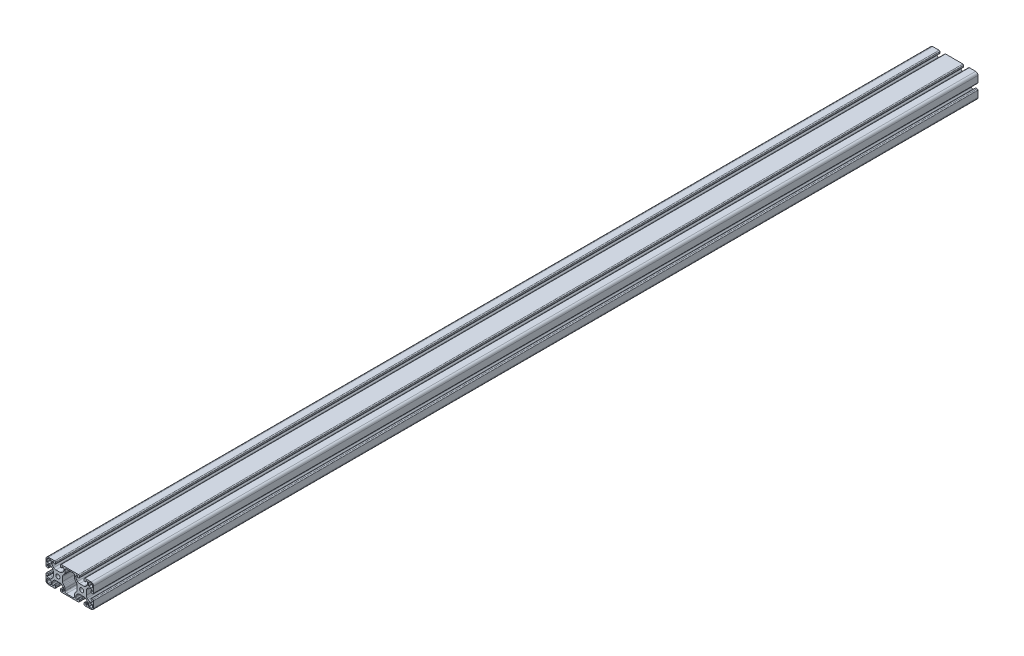
SolidWorks part; units mm, degrees
ref_plane "Plan de face" through (0, 0, 0) normal (0, 0, 1) x (1, 0, 0)
ref_plane "Plan de dessus" through (0, 0, 0) normal (0, 1, 0) x (1, 0, 0)
ref_plane "Plan de droite" through (0, 0, 0) normal (1, 0, 0) x (0, 0, -1)
ref_plane "Plan1" through (0, 0, 20) normal (0, 0, 1) x (1, 0, 0)
sketch "Esquisse1" plane through (0, 0, 20) normal (0, 0, 1) x (1, 0, 0)
  line L0 (66.5, 4.5) -> (65, 4.5)
  line L1 (64, 3.5) -> (64, 1.5)
  line L2 (65.5, 0) -> (76, 0)
  line L3 (80, 4) -> (80, 14.5)
  line L4 (78.5, 16) -> (76.5, 16)
  line L5 (75.5, 15) -> (75.5, 13.5)
  line L6 (76, 13) -> (77.5, 13)
  line L7 (75.5, 10) -> (74.1924, 10)
  line L8 (70.6569, 11.4645) -> (69.2145, 12.9069)
  line L9 (67.75, 16.4424) -> (67.75, 23.5576)
  line L10 (69.2145, 27.0931) -> (70.6569, 28.5355)
  line L11 (74.1924, 30) -> (75.5, 30)
  line L12 (77.5, 27) -> (76, 27)
  line L13 (75.5, 26.5) -> (75.5, 25)
  line L14 (76.5, 24) -> (78.5, 24)
  line L15 (80, 25.5) -> (80, 36)
  line L16 (76, 40) -> (65.5, 40)
  line L17 (64, 38.5) -> (64, 36.5)
  line L18 (65, 35.5) -> (66.5, 35.5)
  line L19 (67, 36) -> (67, 37.5)
  line L20 (70, 35.5) -> (70, 34.1924)
  line L21 (68.5355, 30.6569) -> (67.0931, 29.2145)
  line L22 (63.5576, 27.75) -> (56.4424, 27.75)
  line L23 (52.9069, 29.2145) -> (51.4645, 30.6569)
  line L24 (50, 34.1924) -> (50, 35.5)
  line L25 (53, 37.5) -> (53, 36)
  line L26 (53.5, 35.5) -> (55, 35.5)
  line L27 (56, 36.5) -> (56, 38.5)
  line L28 (54.5, 40) -> (25.5, 40)
  line L29 (24, 38.5) -> (24, 36.5)
  line L30 (25, 35.5) -> (26.5, 35.5)
  line L31 (27, 36) -> (27, 37.5)
  line L32 (30, 35.5) -> (30, 34.1924)
  line L33 (28.5355, 30.6569) -> (27.0931, 29.2145)
  line L34 (23.5576, 27.75) -> (16.4424, 27.75)
  line L35 (12.9069, 29.2145) -> (11.4645, 30.6569)
  line L36 (10, 34.1924) -> (10, 35.5)
  line L37 (13, 37.5) -> (13, 36)
  line L38 (13.5, 35.5) -> (15, 35.5)
  line L39 (16, 36.5) -> (16, 38.5)
  line L40 (14.5, 40) -> (4, 40)
  line L41 (0, 36) -> (0, 25.5)
  line L42 (1.5, 24) -> (3.5, 24)
  line L43 (4.5, 25) -> (4.5, 26.5)
  line L44 (4, 27) -> (2.5, 27)
  line L45 (4.5, 30) -> (5.8076, 30)
  line L46 (9.3431, 28.5355) -> (10.7855, 27.0931)
  line L47 (12.25, 23.5576) -> (12.25, 16.4424)
  line L48 (10.7855, 12.9069) -> (9.3431, 11.4645)
  line L49 (5.8076, 10) -> (4.5, 10)
  line L50 (2.5, 13) -> (4, 13)
  line L51 (4.5, 13.5) -> (4.5, 15)
  line L52 (3.5, 16) -> (1.5, 16)
  line L53 (0, 14.5) -> (0, 4)
  line L54 (4, 0) -> (14.5, 0)
  line L55 (16, 1.5) -> (16, 3.5)
  line L56 (15, 4.5) -> (13.5, 4.5)
  line L57 (13, 4) -> (13, 2.5)
  line L58 (10, 4.5) -> (10, 5.8076)
  line L59 (11.4645, 9.3431) -> (12.9069, 10.7855)
  line L60 (16.4424, 12.25) -> (23.5576, 12.25)
  line L61 (27.0931, 10.7855) -> (28.5355, 9.3431)
  line L62 (30, 5.8076) -> (30, 4.5)
  line L63 (27, 2.5) -> (27, 4)
  line L64 (26.5, 4.5) -> (25, 4.5)
  line L65 (24, 3.5) -> (24, 1.5)
  line L66 (25.5, 0) -> (54.5, 0)
  line L67 (56, 1.5) -> (56, 3.5)
  line L68 (55, 4.5) -> (53.5, 4.5)
  line L69 (53, 4) -> (53, 2.5)
  line L70 (50, 4.5) -> (50, 5.8076)
  line L71 (51.4645, 9.3431) -> (52.9069, 10.7855)
  line L72 (56.4424, 12.25) -> (63.5576, 12.25)
  line L73 (67.0931, 10.7855) -> (68.5355, 9.3431)
  line L74 (70, 5.8076) -> (70, 4.5)
  line L75 (67, 2.5) -> (67, 4)
  line L76 (31.8, 4.5) -> (31.8, 8.2503)
  line L77 (30.3355, 11.7858) -> (29.2145, 12.9069)
  line L78 (27.75, 16.4424) -> (27.75, 23.5576)
  line L79 (29.2145, 27.0931) -> (30.3355, 28.2142)
  line L80 (31.8, 31.7497) -> (31.8, 35.5)
  line L81 (34.3, 38) -> (45.7, 38)
  line L82 (48.2, 35.5) -> (48.2, 31.7497)
  line L83 (49.6645, 28.2142) -> (50.7855, 27.0931)
  line L84 (52.25, 23.5576) -> (52.25, 16.4424)
  line L85 (50.7855, 12.9069) -> (49.6645, 11.7858)
  line L86 (48.2, 8.2503) -> (48.2, 4.5)
  line L87 (45.7, 2) -> (34.3, 2)
  line L88 (7.7, 1.8) -> (4, 1.8)
  line L89 (1.8, 4) -> (1.8, 7.7)
  line L90 (2.3, 8.2) -> (7.7, 8.2)
  line L91 (8.2, 7.7) -> (8.2, 2.3)
  line L92 (72.3, 38.2) -> (76, 38.2)
  line L93 (78.2, 36) -> (78.2, 32.3)
  line L94 (77.7, 31.8) -> (72.3, 31.8)
  line L95 (71.8, 32.3) -> (71.8, 37.7)
  line L96 (78.2, 7.7) -> (78.2, 4)
  line L97 (76, 1.8) -> (72.3, 1.8)
  line L98 (71.8, 2.3) -> (71.8, 7.7)
  line L99 (72.3, 8.2) -> (77.7, 8.2)
  line L100 (1.8, 32.3) -> (1.8, 36)
  line L101 (4, 38.2) -> (7.7, 38.2)
  line L102 (8.2, 37.7) -> (8.2, 32.3)
  line L103 (7.7, 31.8) -> (2.3, 31.8)
  arc A0 (67, 4) -> (66.5, 4.5) centre (66.5, 4) ccw
  arc A1 (65, 4.5) -> (64, 3.5) centre (65, 3.5) ccw
  arc A2 (64, 1.5) -> (65.5, 0) centre (65.5, 1.5) ccw
  arc A3 (76, 0) -> (80, 4) centre (76, 4) ccw
  arc A4 (80, 14.5) -> (78.5, 16) centre (78.5, 14.5) ccw
  arc A5 (76.5, 16) -> (75.5, 15) centre (76.5, 15) ccw
  arc A6 (75.5, 13.5) -> (76, 13) centre (76, 13.5) ccw
  arc A7 (77.5, 13) -> (78, 12.5) centre (77.5, 12.5) cw
  arc A8 (78, 12.5) -> (75.5, 10) centre (75.5, 12.5) cw
  arc A9 (74.1924, 10) -> (70.6569, 11.4645) centre (74.1924, 15) cw
  arc A10 (69.2145, 12.9069) -> (67.75, 16.4424) centre (72.75, 16.4424) cw
  arc A11 (67.75, 23.5576) -> (69.2145, 27.0931) centre (72.75, 23.5576) cw
  arc A12 (70.6569, 28.5355) -> (74.1924, 30) centre (74.1924, 25) cw
  arc A13 (75.5, 30) -> (78, 27.5) centre (75.5, 27.5) cw
  arc A14 (78, 27.5) -> (77.5, 27) centre (77.5, 27.5) cw
  arc A15 (76, 27) -> (75.5, 26.5) centre (76, 26.5) ccw
  arc A16 (75.5, 25) -> (76.5, 24) centre (76.5, 25) ccw
  arc A17 (78.5, 24) -> (80, 25.5) centre (78.5, 25.5) ccw
  arc A18 (80, 36) -> (76, 40) centre (76, 36) ccw
  arc A19 (65.5, 40) -> (64, 38.5) centre (65.5, 38.5) ccw
  arc A20 (64, 36.5) -> (65, 35.5) centre (65, 36.5) ccw
  arc A21 (66.5, 35.5) -> (67, 36) centre (66.5, 36) ccw
  arc A22 (67, 37.5) -> (67.5, 38) centre (67.5, 37.5) cw
  arc A23 (67.5, 38) -> (70, 35.5) centre (67.5, 35.5) cw
  arc A24 (70, 34.1924) -> (68.5355, 30.6569) centre (65, 34.1924) cw
  arc A25 (67.0931, 29.2145) -> (63.5576, 27.75) centre (63.5576, 32.75) cw
  arc A26 (56.4424, 27.75) -> (52.9069, 29.2145) centre (56.4424, 32.75) cw
  arc A27 (51.4645, 30.6569) -> (50, 34.1924) centre (55, 34.1924) cw
  arc A28 (50, 35.5) -> (52.5, 38) centre (52.5, 35.5) cw
  arc A29 (52.5, 38) -> (53, 37.5) centre (52.5, 37.5) cw
  arc A30 (53, 36) -> (53.5, 35.5) centre (53.5, 36) ccw
  arc A31 (55, 35.5) -> (56, 36.5) centre (55, 36.5) ccw
  arc A32 (56, 38.5) -> (54.5, 40) centre (54.5, 38.5) ccw
  arc A33 (25.5, 40) -> (24, 38.5) centre (25.5, 38.5) ccw
  arc A34 (24, 36.5) -> (25, 35.5) centre (25, 36.5) ccw
  arc A35 (26.5, 35.5) -> (27, 36) centre (26.5, 36) ccw
  arc A36 (27, 37.5) -> (27.5, 38) centre (27.5, 37.5) cw
  arc A37 (27.5, 38) -> (30, 35.5) centre (27.5, 35.5) cw
  arc A38 (30, 34.1924) -> (28.5355, 30.6569) centre (25, 34.1924) cw
  arc A39 (27.0931, 29.2145) -> (23.5576, 27.75) centre (23.5576, 32.75) cw
  arc A40 (16.4424, 27.75) -> (12.9069, 29.2145) centre (16.4424, 32.75) cw
  arc A41 (11.4645, 30.6569) -> (10, 34.1924) centre (15, 34.1924) cw
  arc A42 (10, 35.5) -> (12.5, 38) centre (12.5, 35.5) cw
  arc A43 (12.5, 38) -> (13, 37.5) centre (12.5, 37.5) cw
  arc A44 (13, 36) -> (13.5, 35.5) centre (13.5, 36) ccw
  arc A45 (15, 35.5) -> (16, 36.5) centre (15, 36.5) ccw
  arc A46 (16, 38.5) -> (14.5, 40) centre (14.5, 38.5) ccw
  arc A47 (4, 40) -> (0, 36) centre (4, 36) ccw
  arc A48 (0, 25.5) -> (1.5, 24) centre (1.5, 25.5) ccw
  arc A49 (3.5, 24) -> (4.5, 25) centre (3.5, 25) ccw
  arc A50 (4.5, 26.5) -> (4, 27) centre (4, 26.5) ccw
  arc A51 (2.5, 27) -> (2, 27.5) centre (2.5, 27.5) cw
  arc A52 (2, 27.5) -> (4.5, 30) centre (4.5, 27.5) cw
  arc A53 (5.8076, 30) -> (9.3431, 28.5355) centre (5.8076, 25) cw
  arc A54 (10.7855, 27.0931) -> (12.25, 23.5576) centre (7.25, 23.5576) cw
  arc A55 (12.25, 16.4424) -> (10.7855, 12.9069) centre (7.25, 16.4424) cw
  arc A56 (9.3431, 11.4645) -> (5.8076, 10) centre (5.8076, 15) cw
  arc A57 (4.5, 10) -> (2, 12.5) centre (4.5, 12.5) cw
  arc A58 (2, 12.5) -> (2.5, 13) centre (2.5, 12.5) cw
  arc A59 (4, 13) -> (4.5, 13.5) centre (4, 13.5) ccw
  arc A60 (4.5, 15) -> (3.5, 16) centre (3.5, 15) ccw
  arc A61 (1.5, 16) -> (0, 14.5) centre (1.5, 14.5) ccw
  arc A62 (0, 4) -> (4, 0) centre (4, 4) ccw
  arc A63 (14.5, 0) -> (16, 1.5) centre (14.5, 1.5) ccw
  arc A64 (16, 3.5) -> (15, 4.5) centre (15, 3.5) ccw
  arc A65 (13.5, 4.5) -> (13, 4) centre (13.5, 4) ccw
  arc A66 (13, 2.5) -> (12.5, 2) centre (12.5, 2.5) cw
  arc A67 (12.5, 2) -> (10, 4.5) centre (12.5, 4.5) cw
  arc A68 (10, 5.8076) -> (11.4645, 9.3431) centre (15, 5.8076) cw
  arc A69 (12.9069, 10.7855) -> (16.4424, 12.25) centre (16.4424, 7.25) cw
  arc A70 (23.5576, 12.25) -> (27.0931, 10.7855) centre (23.5576, 7.25) cw
  arc A71 (28.5355, 9.3431) -> (30, 5.8076) centre (25, 5.8076) cw
  arc A72 (30, 4.5) -> (27.5, 2) centre (27.5, 4.5) cw
  arc A73 (27.5, 2) -> (27, 2.5) centre (27.5, 2.5) cw
  arc A74 (27, 4) -> (26.5, 4.5) centre (26.5, 4) ccw
  arc A75 (25, 4.5) -> (24, 3.5) centre (25, 3.5) ccw
  arc A76 (24, 1.5) -> (25.5, 0) centre (25.5, 1.5) ccw
  arc A77 (54.5, 0) -> (56, 1.5) centre (54.5, 1.5) ccw
  arc A78 (56, 3.5) -> (55, 4.5) centre (55, 3.5) ccw
  arc A79 (53.5, 4.5) -> (53, 4) centre (53.5, 4) ccw
  arc A80 (53, 2.5) -> (52.5, 2) centre (52.5, 2.5) cw
  arc A81 (52.5, 2) -> (50, 4.5) centre (52.5, 4.5) cw
  arc A82 (50, 5.8076) -> (51.4645, 9.3431) centre (55, 5.8076) cw
  arc A83 (52.9069, 10.7855) -> (56.4424, 12.25) centre (56.4424, 7.25) cw
  arc A84 (63.5576, 12.25) -> (67.0931, 10.7855) centre (63.5576, 7.25) cw
  arc A85 (68.5355, 9.3431) -> (70, 5.8076) centre (65, 5.8076) cw
  arc A86 (70, 4.5) -> (67.5, 2) centre (67.5, 4.5) cw
  arc A87 (67.5, 2) -> (67, 2.5) centre (67.5, 2.5) cw
  circle A88 centre (20, 20) radius 3.4
  circle A89 centre (60, 20) radius 3.4
  arc A90 (34.3, 2) -> (31.8, 4.5) centre (34.3, 4.5) cw
  arc A91 (31.8, 8.2503) -> (30.3355, 11.7858) centre (26.8, 8.2503) ccw
  arc A92 (29.2145, 12.9069) -> (27.75, 16.4424) centre (32.75, 16.4424) cw
  arc A93 (27.75, 23.5576) -> (29.2145, 27.0931) centre (32.75, 23.5576) cw
  arc A94 (30.3355, 28.2142) -> (31.8, 31.7497) centre (26.8, 31.7497) ccw
  arc A95 (31.8, 35.5) -> (34.3, 38) centre (34.3, 35.5) cw
  arc A96 (45.7, 38) -> (48.2, 35.5) centre (45.7, 35.5) cw
  arc A97 (48.2, 31.7497) -> (49.6645, 28.2142) centre (53.2, 31.7497) ccw
  arc A98 (50.7855, 27.0931) -> (52.25, 23.5576) centre (47.25, 23.5576) cw
  arc A99 (52.25, 16.4424) -> (50.7855, 12.9069) centre (47.25, 16.4424) cw
  arc A100 (49.6645, 11.7858) -> (48.2, 8.2503) centre (53.2, 8.2503) ccw
  arc A101 (48.2, 4.5) -> (45.7, 2) centre (45.7, 4.5) cw
  arc A102 (8.2, 2.3) -> (7.7, 1.8) centre (7.7, 2.3) cw
  arc A103 (4, 1.8) -> (1.8, 4) centre (4, 4) cw
  arc A104 (1.8, 7.7) -> (2.3, 8.2) centre (2.3, 7.7) cw
  arc A105 (7.7, 8.2) -> (8.2, 7.7) centre (7.7, 7.7) cw
  arc A106 (71.8, 37.7) -> (72.3, 38.2) centre (72.3, 37.7) cw
  arc A107 (76, 38.2) -> (78.2, 36) centre (76, 36) cw
  arc A108 (78.2, 32.3) -> (77.7, 31.8) centre (77.7, 32.3) cw
  arc A109 (72.3, 31.8) -> (71.8, 32.3) centre (72.3, 32.3) cw
  arc A110 (77.7, 8.2) -> (78.2, 7.7) centre (77.7, 7.7) cw
  arc A111 (78.2, 4) -> (76, 1.8) centre (76, 4) cw
  arc A112 (72.3, 1.8) -> (71.8, 2.3) centre (72.3, 2.3) cw
  arc A113 (71.8, 7.7) -> (72.3, 8.2) centre (72.3, 7.7) cw
  arc A114 (2.3, 31.8) -> (1.8, 32.3) centre (2.3, 32.3) cw
  arc A115 (1.8, 36) -> (4, 38.2) centre (4, 36) cw
  arc A116 (7.7, 38.2) -> (8.2, 37.7) centre (7.7, 37.7) cw
  arc A117 (8.2, 32.3) -> (7.7, 31.8) centre (7.7, 32.3) cw
extrude "Boss.-Extru.1" add sketch "Esquisse1" against normal blind 1487
